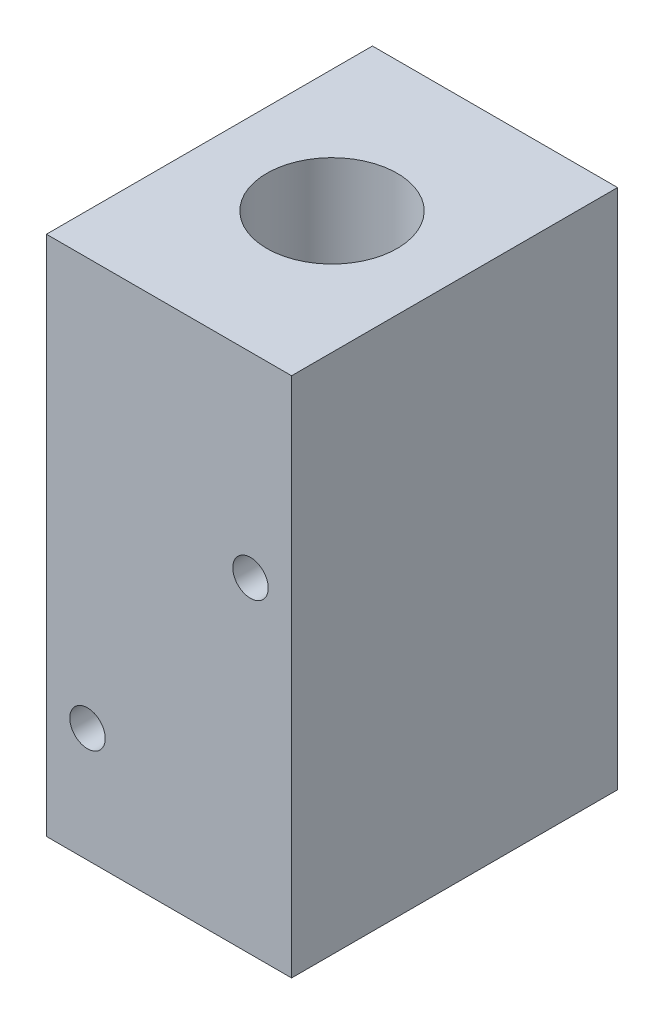
SolidWorks part; units mm, degrees
material "Epoxy, Unfilled"
ref_plane "Front Plane" through (0, 0, 0) normal (0, 0, 1) x (1, 0, 0)
ref_plane "Top Plane" through (0, 0, 0) normal (0, 1, 0) x (1, 0, 0)
ref_plane "Right Plane" through (0, 0, 0) normal (1, 0, 0) x (0, 0, -1)
sketch "Sketch1" plane through (0, 0, 0) normal (1, 0, 0) x (0, 0, -1)
  line L7 (15.875, -50.8) -> (-15.875, -50.8)
  line L8 (15.875, -50.8) -> (15.875, 0)
  line L9 (15.875, 0) -> (-15.875, 0)
  line L10 (-15.875, -50.8) -> (-15.875, 0)
  line L11 (15.875, -50.8) -> (-15.875, 0) construction
  line L12 (15.875, 0) -> (-15.875, -50.8) construction
  point P0 (0, 0)
  point P9 (0, -25.4)
  dimension "D5" = 31.75
  dimension "D6" = 50.8
extrude "Boss-Extrude1" add sketch "Sketch1" along normal blind 11.938 and the other way blind 11.938 contours L9 L10 L7 L8
sketch "Sketch3" plane through (0, 0, 15.875) normal (0, 0, 1) x (1, 0, 0)
  line L0 (-11.938, 0) -> (11.938, 0) construction
  line L1 (-7.9375, -19.05) -> (7.9375, -19.05) construction
  line L2 (-7.9375, -19.05) -> (-7.9375, -39.6748) construction
  line L3 (-7.9375, -39.6748) -> (7.9375, -39.6748) construction
  line L4 (7.9375, -39.6748) -> (7.9375, -19.05) construction
  circle A0 centre (-7.9375, -19.05) radius 1.7272
  circle A1 centre (7.9375, -19.05) radius 1.7272
  circle A2 centre (7.9375, -39.6748) radius 1.7272
  circle A3 centre (-7.9375, -39.6748) radius 1.7272
  point P10 (0, -19.05)
  dimension "D1" = 19.05
  dimension "D4" = 3.4544
  dimension "D2" = 20.6248
  dimension "D3" = 15.875
extrude "Cut-Extrude2" cut sketch "Sketch3" against normal blind 3.175 and the other way through all contours A1 | A3
sketch "Sketch4" plane through (0, 0, 0) normal (0, 1, 0) x (1, 0, 0)
  circle A0 centre (0, 0) radius 6.35
  dimension "D1" = 12.7
extrude "Cut-Extrude3" cut sketch "Sketch4" against normal blind 38.1
